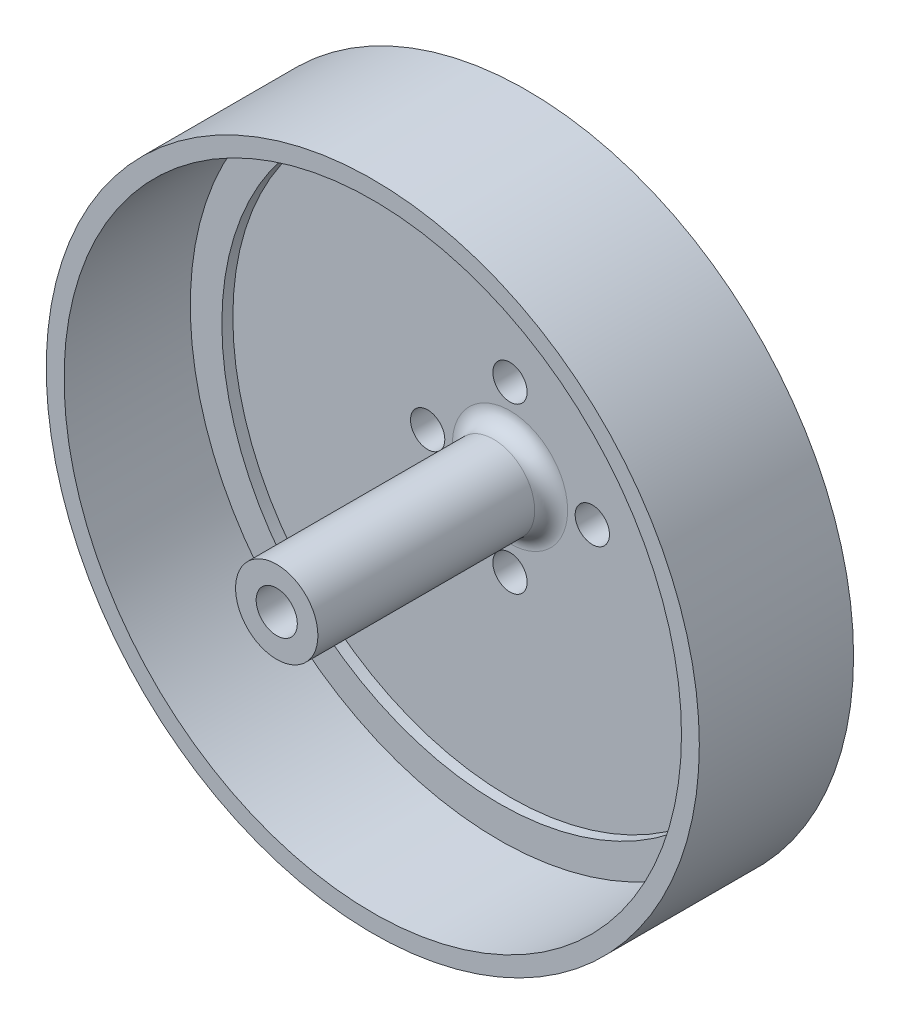
SolidWorks part; units mm, degrees
other "Marca1"
sketch "Croquis3" plane through (-23.8, -23.8, -4) normal (-0.3933, -0.8304, -0.3947) x (-0.8044, 0.5187, -0.2897)
material "Plain Carbon Steel"
ref_plane "Front Plane" through (0, 0, 0) normal (0, 0, 1) x (1, 0, 0)
ref_plane "Top Plane" through (0, 0, 0) normal (0, 1, 0) x (1, 0, 0)
ref_plane "Right Plane" through (0, 0, 0) normal (1, 0, 0) x (0, 0, -1)
sketch "Sketch1" plane through (0, 0, 0) normal (0, 0, 1) x (1, 0, 0)
  circle A0 centre (0, 0) radius 23.8
  dimension "D2" = 47.6
extrude "Boss-Extrude1" add sketch "Sketch1" along normal blind 2.3
sketch "Sketch2" plane through (0, 0, 2.3) normal (0, 0, 1) x (1, 0, 0)
  circle A0 centre (0, 0) radius 23.8
  circle A1 centre (0, 0) radius 20.2
  dimension "D1" = 40.4
extrude "Boss-Extrude2" add sketch "Sketch2" along normal blind 10
sketch "Sketch3" plane through (0, 0, 2.3) normal (0, 0, 1) x (1, 0, 0)
  circle A0 centre (0, 0) radius 3
extrude "Boss-Extrude3" add sketch "Sketch3" along normal blind 17
chamfer "Chamfer1" distance 6 angle 10 1 edges at (23.8, 0, 0)
sketch "Sketch4" plane through (0, 0, 0) normal (0, 0, -1) x (-1, 0, 0)
  circle A0 centre (0, 0) radius 6 construction
  circle A1 centre (6, 0) radius 1.25
  circle A2 centre (0, -6) radius 1.25
  circle A3 centre (-6, 0) radius 1.25
  circle A4 centre (0, 6) radius 1.25
  point P14 (0, 0)
  dimension "D1" = 12
  dimension "D2" = 4
  dimension "D3" = 2.5
extrude "Cut-Extrude1" cut sketch "Sketch4" against normal blind 15
sketch "Sketch6" plane through (0, 0, 12.3) normal (0, 0, 1) x (1, 0, 0)
  circle A0 centre (0, 0) radius 22.5
  circle A1 centre (0, 0) radius 20.2
extrude "Cut-Extrude3" cut sketch "Sketch6" against normal blind 9.2
sketch "Sketch7" plane through (0, 0, 19.3) normal (0, 0, 1) x (1, 0, 0)
  circle A0 centre (0, 0) radius 1.5
  dimension "D1" = 3
extrude "Cut-Extrude4" cut sketch "Sketch7" against normal blind 5
fillet "Redondeo1" radius 1.2 1 edges at (3, 0, 2.3)
sketch "Croquis1" plane through (0, 0, 0) normal (0, 0, -1) x (-1, 0, 0)
  circle A0 centre (0, 0) radius 9.3393
  circle A1 centre (0, 6) radius 1.25
  circle A2 centre (6, 0) radius 1.25
  circle A3 centre (0, -6) radius 1.25
  circle A4 centre (-6, 0) radius 1.25
  circle A5 centre (-6, 0) radius 1.25 construction
extrude "Saliente-Extruir1" add sketch "Croquis1" along normal blind 1.6
sketch "Croquis2" plane through (0, 0, -1.6) normal (0, 0, -1) x (-1, 0, 0)
  circle A0 centre (0, 0) radius 2
  dimension "D1" = 4
extrude "Saliente-Extruir2" add sketch "Croquis2" along normal blind 3
